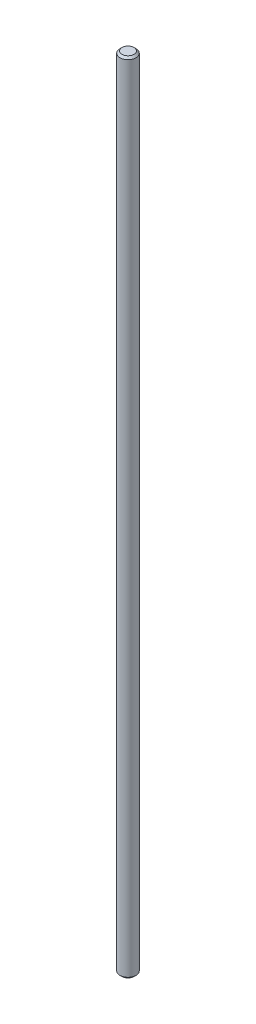
SolidWorks part; units mm, degrees
ref_plane "Front Plane" through (0, 0, 0) normal (0, 0, 1) x (1, 0, 0)
ref_plane "Top Plane" through (0, 0, 0) normal (0, 1, 0) x (1, 0, 0)
ref_plane "Right Plane" through (0, 0, 0) normal (1, 0, 0) x (0, 0, -1)
sketch "Sketch1" plane through (0, 0, 0) normal (0, 1, 0) x (1, 0, 0)
  circle A0 centre (0, 0) radius 4
  dimension "D1" = 8
extrude "Boss-Extrude1" add sketch "Sketch1" along normal blind 400
chamfer "Chamfer1" distance 1 angle 45 2 edges at (0, 400, 4) (0, 0, 4)
